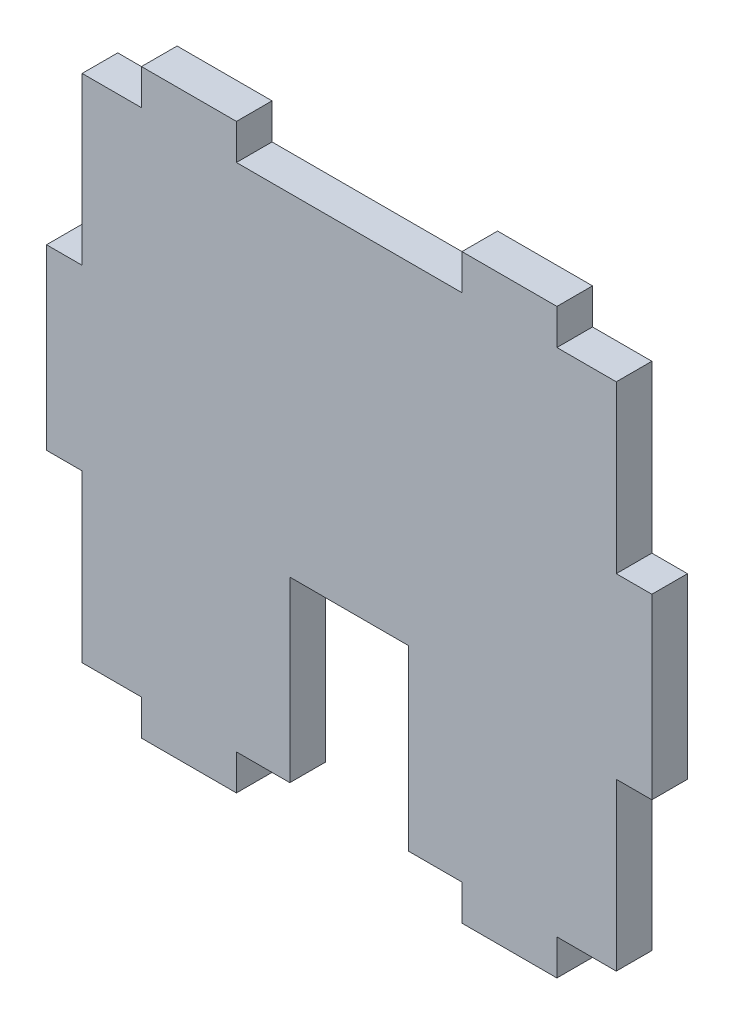
SolidWorks part; units mm, degrees
ref_plane "前视基准面" through (0, 0, 0) normal (0, 0, 1) x (1, 0, 0)
ref_plane "上视基准面" through (0, 0, 0) normal (0, 1, 0) x (1, 0, 0)
ref_plane "右视基准面" through (0, 0, 0) normal (1, 0, 0) x (0, 0, -1)
other "Configuration Table"
sketch "草图1" plane through (0, 0, 0) normal (0, 0, 1) x (1, 0, 0)
  line L0 (0, 10.3147) -> (0, -11.2713) construction
  line L1 (-22.5, 21.5) -> (22.5, 21.5)
  line L2 (-22.5, 21.5) -> (-22.5, -21.5)
  line L3 (-22.5, -21.5) -> (22.5, -21.5)
  line L4 (22.5, 21.5) -> (22.5, -21.5)
  line L5 (-22.5, 21.5) -> (22.5, -21.5) construction
  line L6 (-22.5, -21.5) -> (22.5, 21.5) construction
  line L7 (22.5, 7.5) -> (25.5, 7.5)
  line L8 (22.5, 7.5) -> (22.5, -7.5)
  line L9 (22.5, -7.5) -> (25.5, -7.5)
  line L10 (25.5, 7.5) -> (25.5, -7.5)
  line L11 (-22.5, -7.5) -> (-25.5, -7.5)
  line L12 (-25.5, 7.5) -> (-25.5, -7.5)
  line L13 (-22.5, 7.5) -> (-25.5, 7.5)
  line L14 (-22.5, 7.5) -> (-22.5, -7.5)
  line L15 (17.5, 24.5) -> (9.5, 24.5)
  line L16 (-17.5, 21.5) -> (-9.5, 21.5)
  line L17 (-17.5, 21.5) -> (-17.5, 24.5)
  line L18 (-17.5, 24.5) -> (-9.5, 24.5)
  line L19 (-9.5, 21.5) -> (-9.5, 24.5)
  line L20 (9.5, 21.5) -> (9.5, 24.5)
  line L21 (17.5, 21.5) -> (9.5, 21.5)
  line L22 (17.5, 21.5) -> (17.5, 24.5)
  line L23 (-6.517, 0) -> (4.4558, 0) construction
  line L24 (17.5, -21.5) -> (17.5, -24.5)
  line L25 (17.5, -21.5) -> (9.5, -21.5)
  line L26 (9.5, -21.5) -> (9.5, -24.5)
  line L27 (17.5, -24.5) -> (9.5, -24.5)
  line L28 (-17.5, -24.5) -> (-9.5, -24.5)
  line L29 (-9.5, -21.5) -> (-9.5, -24.5)
  line L30 (-17.5, -21.5) -> (-9.5, -21.5)
  line L31 (-17.5, -21.5) -> (-17.5, -24.5)
  point P0 (0, 0)
  point P10 (25.5, 0)
  dimension "D1" = 45
  dimension "D2" = 43
  dimension "D3" = 3
  dimension "D4" = 15
  dimension "D5" = 3
  dimension "D6" = 8
  dimension "D7" = 9.5
extrude "凸台-拉伸1" add sketch "草图1" along normal blind 3 contours L4 L1 L2 L3 | L1 L19 L18 L17 | L1 L22 L15 L20 | L2 L13 L12 L11 | L10 L7 L4 L9 | L3 L31 L28 L29 | L27 L24 L3 L26
sketch "草图2" plane through (0, 0, 3) normal (0, 0, 1) x (1, 0, 0)
  line L0 (-9.5, -21.5) -> (9.5, -21.5) construction
  line L1 (-5, -6.5) -> (5, -6.5)
  line L2 (-5, -6.5) -> (-5, -21.5)
  line L3 (-5, -21.5) -> (5, -21.5)
  line L4 (5, -6.5) -> (5, -21.5)
  line L5 (-5, -6.5) -> (5, -21.5) construction
  line L6 (-5, -21.5) -> (5, -6.5) construction
  point P0 (0, -14)
  point P7 (0, 0)
  dimension "D1" = 15
  dimension "D2" = 10
extrude "切除-拉伸1" cut sketch "草图2" against normal blind 10
